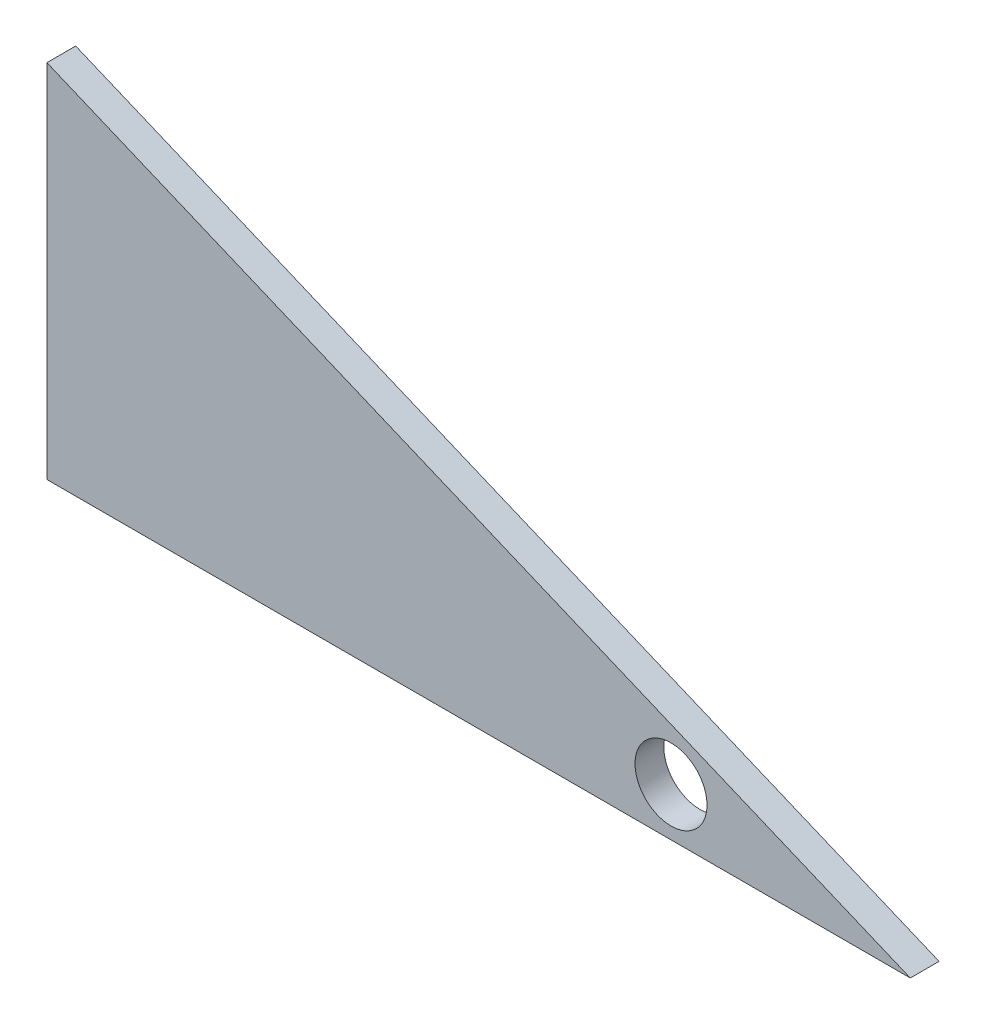
SolidWorks part; units mm, degrees
ref_plane "Front Plane" through (0, 0, 0) normal (0, 0, 1) x (1, 0, 0)
ref_plane "Top Plane" through (0, 0, 0) normal (0, 1, 0) x (1, 0, 0)
ref_plane "Right Plane" through (0, 0, 0) normal (1, 0, 0) x (0, 0, -1)
sketch "Sketch1" plane through (0, 0, 0) normal (0, 0, 1) x (1, 0, 0)
  line L0 (0, 0) -> (0, 47.752)
  line L1 (0, 47.752) -> (114.1953, 0)
  line L2 (114.1953, 0) -> (0, 0)
  circle A0 centre (82.55, 6.35) radius 4.7625
  dimension "D4" = 9.525
  dimension "D1" = 6.35
  dimension "D2" = 47.752
  dimension "D3" = 90
  dimension "D5" = 6.35
  dimension "D6" = 82.55
extrude "Boss-Extrude1" add sketch "Sketch1" along normal blind 3.81
